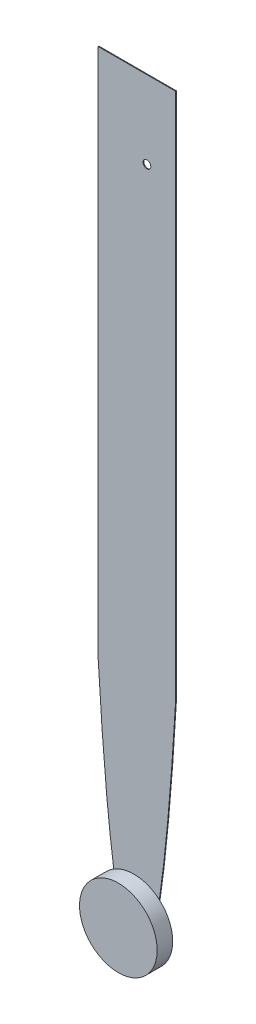
SolidWorks part; units mm, degrees
material "AISI 1020"
ref_plane "Plano frontal" through (0, 0, 0) normal (0, 0, 1) x (1, 0, 0)
ref_plane "Plano superior" through (0, 0, 0) normal (0, 1, 0) x (1, 0, 0)
ref_plane "Plano direito" through (0, 0, 0) normal (1, 0, 0) x (0, 0, -1)
sketch "Esboço1" plane through (0, 0, 0) normal (0, 0, 1) x (1, 0, 0)
  line L2 (-4.618, 68.6748) -> (5.382, 68.6748)
  line L5 (5.382, 68.6748) -> (5.382, 0.7296)
  line L6 (5.382, 0.7296) -> (4.2104, -19.422) construction
  line L7 (4.2104, -19.422) -> (2.5116, -31.2552) construction
  line L8 (2.5116, -31.2552) -> (0.382, -31.3252) construction
  line L9 (0.382, -36.9287) -> (0.382, 47.7314) construction
  line L10 (-4.618, 0.7296) -> (-3.4464, -19.422) construction
  line L11 (-3.4464, -19.422) -> (-1.7476, -31.2552) construction
  line L12 (-4.618, 68.6748) -> (-4.618, 0.7296)
  line L13 (-1.7476, -31.2552) -> (0.382, -31.3252) construction
  spline S0 degree 3 poles (5.382, 0.7296) (4.2104, -19.422) (2.5116, -31.2552) (0.382, -31.3252) knots 0 0 0 0 1 1 1 1
  spline S1 degree 3 poles (-4.618, 0.7296) (-3.4464, -19.422) (-1.7476, -31.2552) (0.382, -31.3252) knots 0 0 0 0 1 1 1 1
  point P10 (0.382, 68.6748)
  dimension "D1" = 100
  dimension "D2" = 10
extrude "Ressalto-extrusão1" add sketch "Esboço1" along normal blind 0.1
sketch "Esboço2" plane through (0, 0, 0.1) normal (0, 0, 1) x (1, 0, 0)
  line L0 (0, -26.3252) -> (0, 0) construction
  circle A0 centre (0, -26.3252) radius 5
  dimension "D1" = 10
  dimension "D2" = 5
extrude "Ressalto-extrusão2" add sketch "Esboço2" along normal blind 2
sketch "Esboço3" plane through (0, 0, 0.1) normal (0, 0, 1) x (1, 0, 0)
  line L0 (5.382, 68.6748) -> (-4.618, 68.6748) construction
  line L1 (5.382, 0.7296) -> (5.382, 68.6748) construction
  circle A0 centre (1.682, 58.6748) radius 0.5
  dimension "D2" = 1
  dimension "D1" = 10
  dimension "D3" = 3.7
extrude "Corte-extrusão1" cut sketch "Esboço3" against normal blind 10
sketch "Esboço4" plane through (0, 0, 0.1) normal (0, 0, 1) x (1, 0, 0)
  circle A0 centre (1.682, 58.6748) radius 0.5 construction
  point P0 (1.682, 59.1748)
